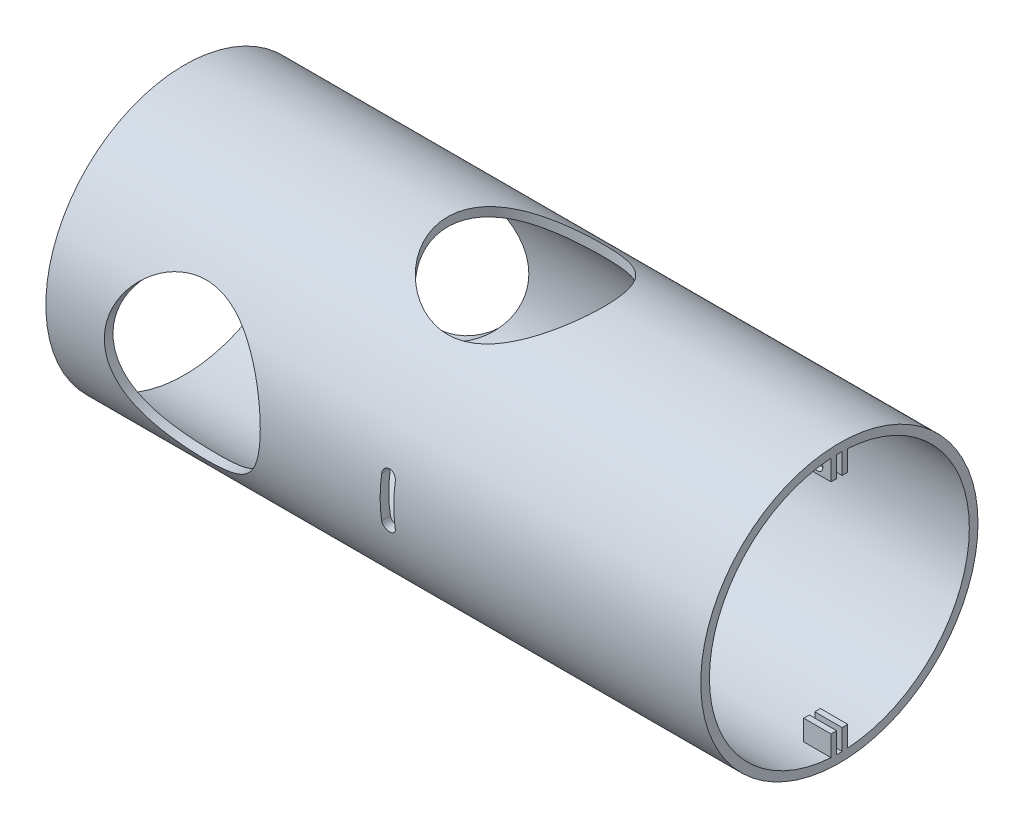
SolidWorks part; units mm, degrees
ref_plane "Front Plane" through (0, 0, 0) normal (0, 0, 1) x (1, 0, 0)
ref_plane "Top Plane" through (0, 0, 0) normal (0, 1, 0) x (1, 0, 0)
ref_plane "Right Plane" through (0, 0, 0) normal (1, 0, 0) x (0, 0, -1)
sketch "Sketch1" plane through (0, 0, 0) normal (0, 1, 0) x (1, 0, 0)
  line L0 (0, 101.6) -> (-480, 101.6)
  line L1 (0, -55) -> (0, 55) construction
  line L2 (0, 95.25) -> (-480, 95.25)
  line L3 (-480, 95.25) -> (-480, 101.6)
  line L6 (0, 95.25) -> (0, 101.6)
  line L7 (-72.3795, 0) -> (-325.7905, 0) construction
  dimension "D1" = 6.35
  dimension "D2" = 101.6
  dimension "D4" = 480
revolve "Revolve1" add sketch "Sketch1" angle 360 about L7
sketch "Sketch2" plane through (0, 0, 0) normal (0, 0, 1) x (1, 0, 0)
  line L0 (55, 0) -> (-55, 0) construction
  line L2 (-480, 101.6) -> (-480, -101.6) construction
  circle A0 centre (-380, 0) radius 57.15
  dimension "D1" = 114.3
  dimension "D2" = 100
extrude "Cut-Extrude1" cut sketch "Sketch2" against normal through all and the other way through all
sketch "Sketch3" plane through (0, 0, 0) normal (0, 1, 0) x (1, 0, 0)
  circle A0 centre (-230, 0) radius 57.15
  dimension "D1" = 114.3
extrude "Cut-Extrude2" cut sketch "Sketch3" against normal through all and the other way through all
sketch "Sketch4" plane through (0, 0, 0) normal (1, 0, 0) x (0, 0, -1)
  line L0 (-2, 96.0633) -> (-2, 79.9977)
  line L1 (-2, 79.9977) -> (-6.1195, 79.9977)
  line L2 (-6.1195, 79.9977) -> (-6.1195, 98.3977)
  line L3 (-6.1195, 98.3977) -> (6.1195, 98.3977)
  line L4 (6.1195, 98.3977) -> (6.1195, 80)
  line L5 (6.1195, 80) -> (2, 80)
  line L6 (2, 80) -> (2, 96.0633)
  line L7 (2, 96.0633) -> (-2, 96.0633)
  line L8 (0, 111.265) -> (0, -111.265) construction
  dimension "D1" = 2
  dimension "D2" = 4
  dimension "D3" = 80
  dimension "D4" = 18.4
  dimension "D5" = 18.3977
extrude "Boss-Extrude1" add sketch "Sketch4" against normal blind 20
mirror "Mirror1" about plane through (0, 0, 0) normal (0, 1, 0) of "Boss-Extrude1"
sketch "Sketch5" plane through (0, 0, 0) normal (0, 0, 1) x (1, 0, 0)
  line L0 (-20, 80) -> (0, 80) construction
  line L1 (0, 80) -> (0, 95.0532) construction
  circle A0 centre (-10, 86) radius 4
  dimension "D1" = 8
  dimension "D2" = 6
  dimension "D3" = 10
extrude "Cut-Extrude3" cut sketch "Sketch5" against normal blind 20 and the other way blind 20
sketch "Sketch6" plane through (0, 0, 0) normal (0, 0, 1) x (1, 0, 0)
  line L0 (55, 0) -> (-55, 0) construction
  line L1 (-480, 101.6) -> (-480, -101.6) construction
  line L2 (-235, -15) -> (-235, 15)
  line L3 (-225, -15) -> (-225, 15)
  arc A0 (-235, -15) -> (-225, -15) centre (-230, -15) ccw
  arc A1 (-225, 15) -> (-235, 15) centre (-230, 15) ccw
  dimension "D1" = 10
  dimension "D2" = 10
  dimension "D3" = 30
  dimension "D4" = 15
  dimension "D5" = 250
extrude "Cut-Extrude4" cut sketch "Sketch6" against normal through all both and the other way through all
